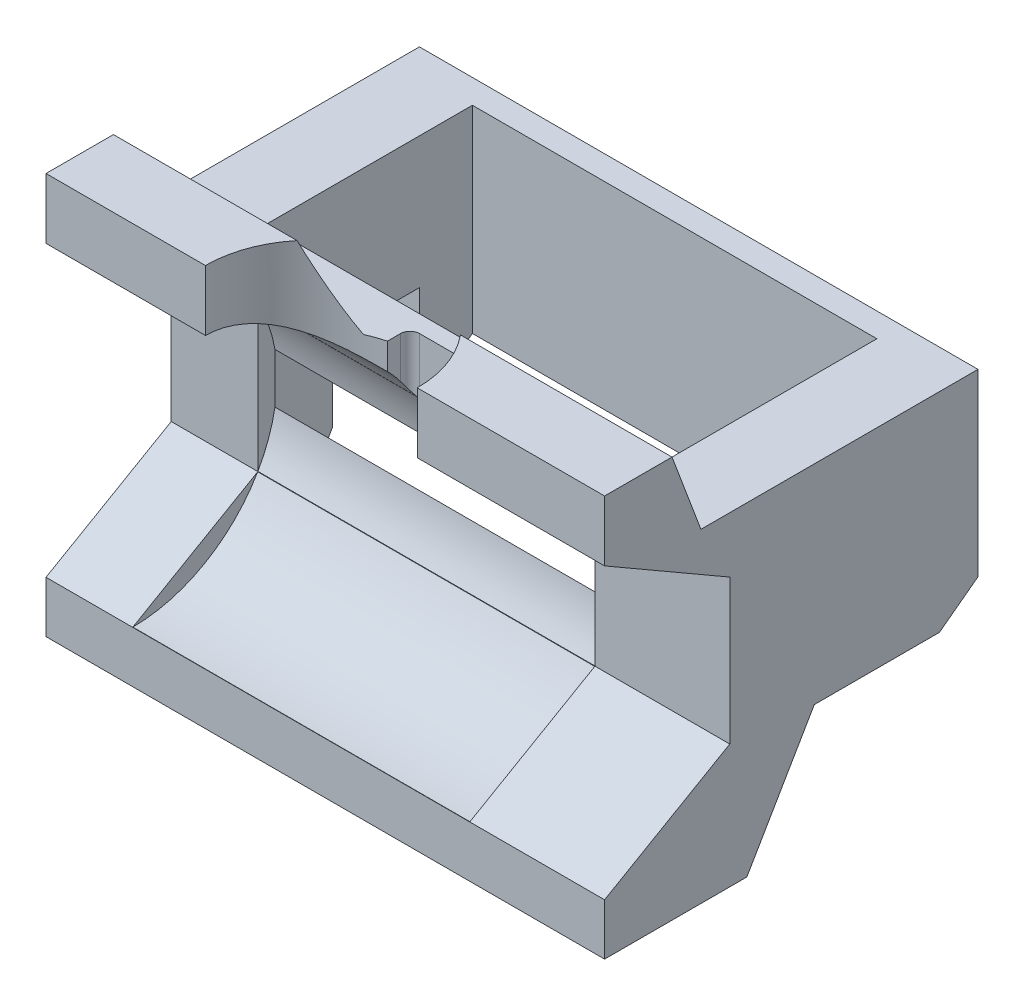
SolidWorks part; units mm, degrees
ref_plane "Front Plane" through (0, 0, 0) normal (0, 0, 1) x (1, 0, 0)
ref_plane "Top Plane" through (0, 0, 0) normal (0, 1, 0) x (1, 0, 0)
ref_plane "Right Plane" through (0, 0, 0) normal (1, 0, 0) x (0, 0, -1)
ref_plane "Plane1" through (0, -25, 0) normal (0, 1, 0) x (1, 0, 0)
sketch "Sketch1" plane through (0, -25, 0) normal (0, 1, 0) x (1, 0, 0)
  line L0 (-4.2598, -25.7738) -> (4.15, -25.7738) construction
  line L1 (29, -25.7738) -> (-29, -25.7738)
  line L2 (29, -25.7738) -> (29, 13)
  line L3 (29, 13) -> (-29, 13)
  line L4 (-29, -25.7738) -> (-29, 13)
  line L5 (29, -25.7738) -> (-29, 13) construction
  line L6 (29, 13) -> (-29, -25.7738) construction
  line L8 (27, 3.8) -> (27, -3.8) construction
  line L9 (-8.46, 10) -> (19.75, 10) construction
  line L10 (-27, -3.8) -> (-27, 3.8) construction
  line L12 (21, 10.5) -> (-21, 10.5)
  line L13 (21, 10.5) -> (21, -11)
  line L14 (21, -11) -> (-21, -11)
  line L15 (-21, 10.5) -> (-21, -11)
  point P0 (0, -6.3869)
  point P5 (21.0423, 11.0063)
  point P9 (-0.0549, -25.7738)
  dimension "D1" = 2
  dimension "D2" = 2.5
  dimension "D3" = 2
  dimension "D4" = 3
  dimension "D5" = 8
  dimension "D6" = 8
  dimension "D7" = 21.5
extrude "Boss-Extrude2" add sketch "Sketch1" along normal up to surface (33.65 mm away)
sketch "Sketch4" plane through (0, 0, 0) normal (1, 0, 0) x (0, 0, -1)
  line L0 (10.5, 8.65) -> (10.5, -25) construction
  line L1 (10.5, -23) -> (-11, -23)
  line L2 (10.5, -23) -> (10.5, 4.65)
  line L3 (10.5, 4.65) -> (-11, 4.65)
  line L4 (-11, -23) -> (-11, 4.65)
  line L5 (-11, 8.65) -> (-11, -25) construction
  line L6 (-11, -25) -> (10.5, -25) construction
  line L7 (13, 8.65) -> (-25.7738, 8.65) construction
  dimension "D1" = 2
  dimension "D2" = 4
extrude "Cut-Extrude1" [suppressed] cut sketch "Sketch4" against normal through all both and the other way through all
sketch "Sketch5" [suppressed] plane through (0, 0, 0) normal (0, 0, 1) x (1, 0, 0)
  line L1 (-21, 4.65) -> (21, 4.65)
  line L2 (-21, 4.65) -> (-21, -19)
  line L3 (-21, -19) -> (21, -19)
  line L4 (21, 4.65) -> (21, -19)
extrude "Cut-Extrude2" [suppressed] cut sketch "Sketch5" against normal through all both and the other way through all
sketch "Sketch6" plane through (29, 0, 0) normal (1, 0, 0) x (0, 0, -1)
  line L0 (-11, -25) -> (-4, -13)
  line L1 (-25.7738, -25) -> (13, -25) construction
  line L2 (-4, -13) -> (9, -13)
  line L3 (9, -13) -> (13, -10)
  line L4 (13, 8.65) -> (13, -25) construction
  line L5 (13, -10) -> (13, -25)
  line L6 (13, -25) -> (-11, -25)
  dimension "D1" = 24
  dimension "D2" = 17
  dimension "D3" = 12
  dimension "D4" = 3
  dimension "D5" = 4
extrude "Cut-Extrude3" cut sketch "Sketch6" against normal through all
sketch "Sketch7" plane through (0, -13, 0) normal (0, -1, 0) x (1, 0, 0)
  line L0 (-21, -9) -> (-21, 4) construction
  line L1 (-21, -5) -> (-25, -5)
  line L2 (-21, -5) -> (-21, 4)
  line L3 (-21, 4) -> (-25, 4)
  line L4 (-25, -5) -> (-25, 4)
  line L5 (-29, 4) -> (-21, 4) construction
  dimension "D1" = 9
extrude "Cut-Extrude4" cut sketch "Sketch7" against normal blind 8
sketch "Sketch8" plane through (-29, 0, 0) normal (-1, 0, 0) x (0, 0, 1)
  line L0 (25.7738, 8.65) -> (25.7738, -25) construction
  line L1 (25.7738, 10.3611) -> (12.7738, 2.8556)
  line L2 (12.7738, 2.8556) -> (12.7738, -12.1556)
  line L3 (12.7738, -12.1556) -> (25.7738, -19.6611)
  line L4 (25.7738, -19.6611) -> (38.7738, -12.1556)
  line L5 (38.7738, -12.1556) -> (38.7738, 2.8556)
  line L6 (38.7738, 2.8556) -> (25.7738, 10.3611)
  circle A0 centre (25.7738, -4.65) radius 13 construction
  point P1 (25.7738, -6.175)
  point P9 (0, 0)
  point P10 (0, 0)
  point P11 (25.7738, -6.175)
  point P12 (6.4586, -4.1888)
  point P13 (0, 0)
  point P14 (0, 0)
  point P15 (0, 0)
  point P16 (0, 0)
  point P18 (0, 0)
  point P19 (0, 0)
  dimension "D1" = 13
sketch "Sketch9" plane through (-29, 0, 0) normal (-1, 0, 0) x (0, 0, 1)
  line L0 (15.7738, 8.65) -> (18.7738, 16.65)
  line L1 (25.7738, 8.65) -> (-13, 8.65) construction
  line L2 (18.7738, 16.65) -> (25.7738, 16.65)
  line L3 (25.7738, 16.65) -> (25.7738, 8.65)
  line L4 (15.7738, 8.65) -> (25.7738, 8.65)
  dimension "D1" = 7
  dimension "D2" = 8
  dimension "D3" = 10
extrude "Boss-Extrude3" add sketch "Sketch9" against normal up to surface (58 mm away) up to face at (29, -9.8143, 4.5068)
extrude "Cut-Extrude5" cut sketch "Sketch8" against normal through all
sketch "Sketch10" plane through (0, 16.65, 0) normal (0, 1, 0) x (1, 0, 0)
  line L0 (29, -25.7738) -> (-29, -25.7738) construction
  line L1 (-4.2, -25.7738) -> (1.3, -25.7738)
  line L2 (-4.2, -25.7738) -> (-4.2, -12.7738)
  line L3 (-4.2, -12.7738) -> (1.3, -12.7738)
  line L4 (1.3, -25.7738) -> (1.3, -12.7738)
  circle A0 centre (-1.45, -25.7738) radius 11
  arc A1 (-7.95, -25.7738) -> (5.05, -25.7738) centre (-1.45, -25.7738) ccw construction
  point P11 (-1.45, -12.7738)
  line M7 (29, -18.7738) -> (-29, -18.7738)
  line M9 (-29, -25.7738) -> (29, -25.7738)
  dimension "D1" = 22
  dimension "D2" = 5.5
  dimension "D3" = 13
extrude "Cut-Extrude6" cut sketch "Sketch10" against normal blind 15 contours A0 L4 L3 L2 | A0 L4 M9 M7 | A0 L4 M7 | L4 A0 L2 M7 | A0 L2 M7 M9 | L4 L2 M9 M7 | L2 A0 M7
fillet "Fillet1" radius 1 2 edges at (1.3, 5.7528, 12.7738) (-4.2, 5.7528, 12.7738)
sketch "Sketch11" plane through (0, 0, 0) normal (1, 0, 0) x (0, 0, -1)
  circle A0 centre (-25.7738, -4.65) radius 15
  dimension "D1" = 30
extrude "Cut-Extrude7" cut sketch "Sketch11" against normal blind 20 and the other way blind 15 contours A0
